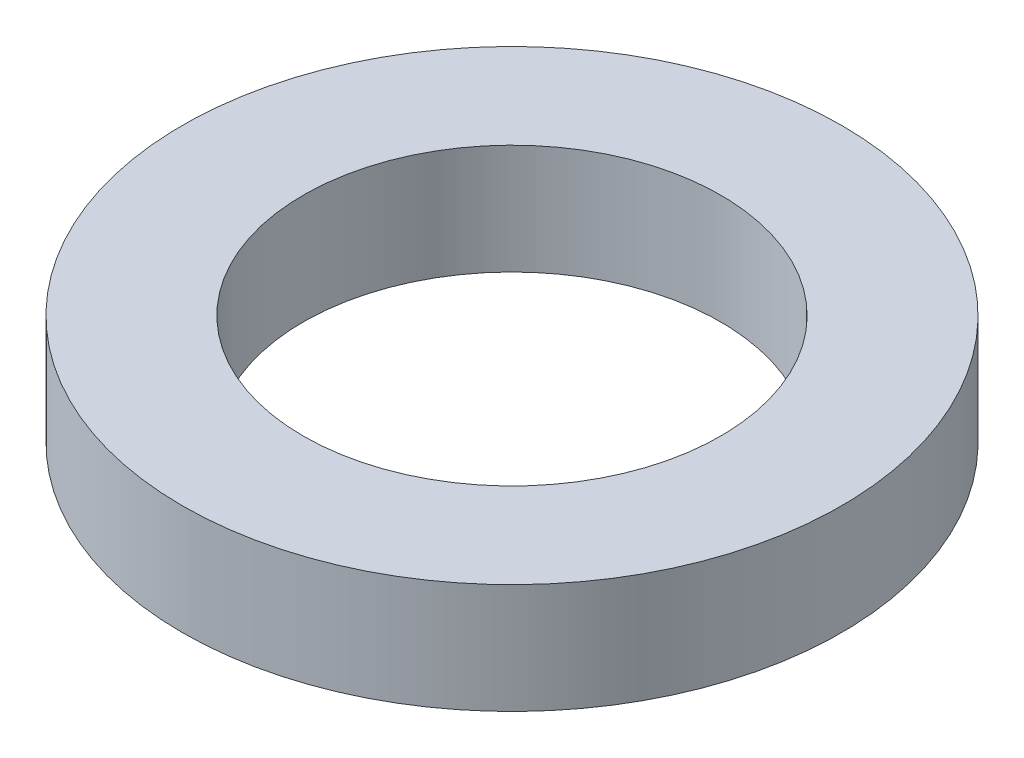
SolidWorks part; units mm, degrees
ref_plane "Front Plane" through (0, 0, 0) normal (0, 0, 1) x (1, 0, 0)
ref_plane "Top Plane" through (0, 0, 0) normal (0, 1, 0) x (1, 0, 0)
ref_plane "Right Plane" through (0, 0, 0) normal (1, 0, 0) x (0, 0, -1)
sketch "Sketch1" plane through (0, 0, 0) normal (0, 1, 0) x (1, 0, 0)
  circle A0 centre (0, 0) radius 3
  circle A1 centre (0, 0) radius 1.9
  dimension "D1" = 6
  dimension "D2" = 3.8
extrude "Boss-Extrude1" add sketch "Sketch1" along normal blind 1
